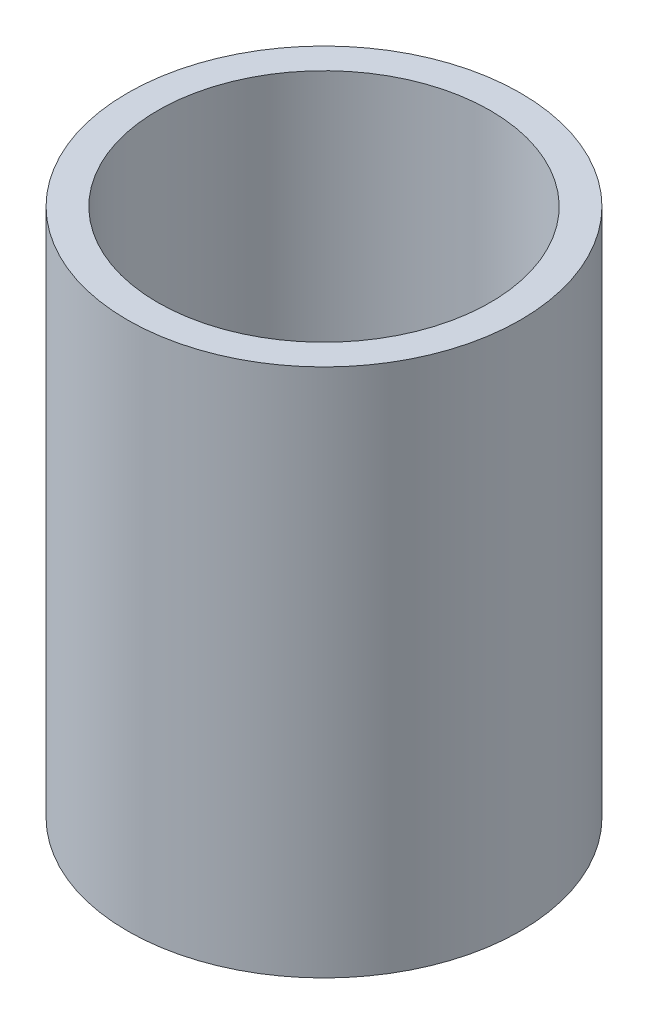
SolidWorks part; units mm, degrees
ref_plane "Front Plane" through (0, 0, 0) normal (0, 0, 1) x (1, 0, 0)
ref_plane "Top Plane" through (0, 0, 0) normal (0, 1, 0) x (1, 0, 0)
ref_plane "Right Plane" through (0, 0, 0) normal (1, 0, 0) x (0, 0, -1)
sketch "Sketch1" plane through (0, 0, 0) normal (0, 1, 0) x (1, 0, 0)
  circle A0 centre (0, 0) radius 52
  dimension "D1" = 104
extrude "Boss-Extrude1" add sketch "Sketch1" along normal blind 140 contours A0
shell "Shell1" thickness 8
sketch "Sketch3" plane through (0, 140, 0) normal (0, 1, 0) x (1, 0, 0)
  circle A0 centre (0, 0) radius 44 construction
  circle A1 centre (0, 0) radius 44
extrude "Cut-Extrude1" cut sketch "Sketch3" against normal blind 40
